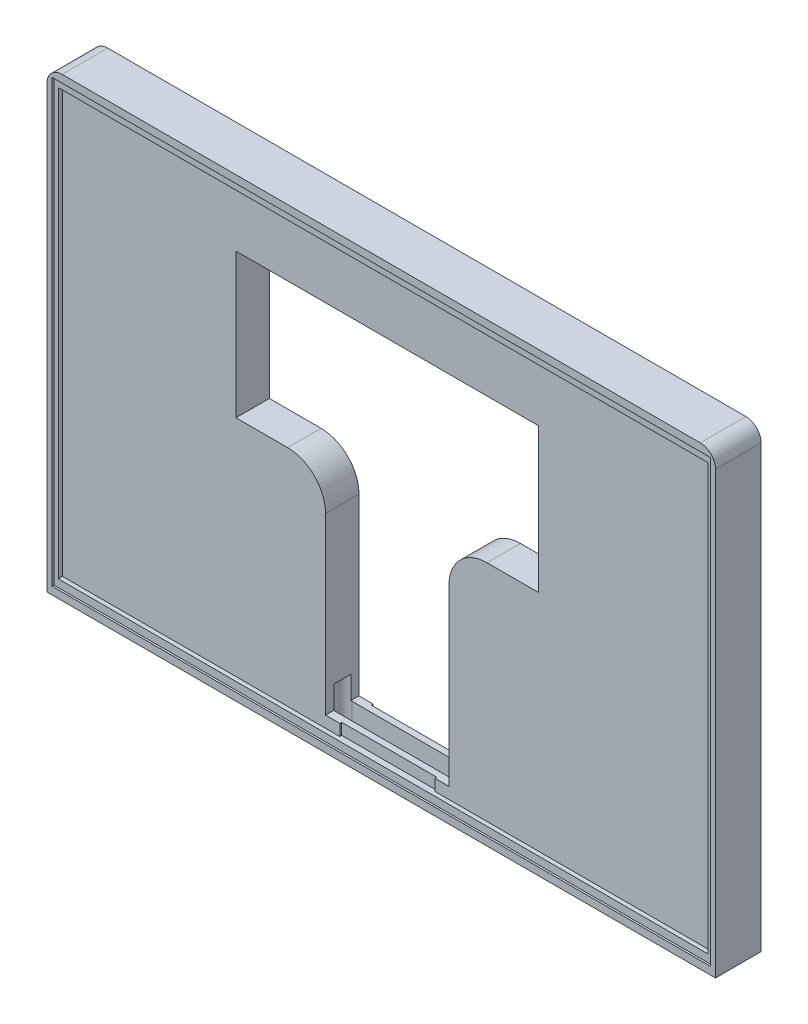
SolidWorks part; units mm, degrees
ref_plane "前视基准面" through (0, 0, 0) normal (0, 0, 1) x (1, 0, 0)
ref_plane "上视基准面" through (0, 0, 0) normal (0, 1, 0) x (1, 0, 0)
ref_plane "右视基准面" through (0, 0, 0) normal (1, 0, 0) x (0, 0, -1)
other "Configuration Table"
sketch "草图1" plane through (0, 0, 0) normal (0, 0, 1) x (1, 0, 0)
  line L0 (-88, 60) -> (-88, -60)
  line L1 (-88, -60) -> (88, -60)
  line L2 (88, -60) -> (88, 60)
  line L3 (88, 60) -> (-88, 60)
  line L4 (0, 145.8225) -> (0, -134.4269) construction
  line L5 (-152.9976, 0) -> (171.9904, 0) construction
  dimension "D1" = 176
  dimension "D2" = 120
extrude "凸台-拉伸1" add sketch "草图1" along normal blind 12
sketch "草图2" plane through (0, 0, 12) normal (0, 0, 1) x (1, 0, 0)
  line L0 (-111.1919, 0) -> (116.8836, 0) construction
  line L1 (0, 67.9619) -> (0, -74.6023) construction
  line L3 (-85.5, 56) -> (85.5, 56)
  line L4 (-85.5, 56) -> (-85.5, -56)
  line L5 (-85.5, -56) -> (85.5, -56)
  line L6 (85.5, 56) -> (85.5, -56)
  line L7 (-85.5, 56) -> (85.5, -56) construction
  line L8 (-85.5, -56) -> (85.5, 56) construction
  point P5 (0, 0)
  dimension "D1" = 171
  dimension "D2" = 112
extrude "切除-拉伸1" cut sketch "草图2" against normal blind 1.6
sketch "草图3" plane through (0, 0, 0) normal (0, 0, -1) x (-1, 0, 0)
  line L0 (-109.5657, 0) -> (110.3788, 0) construction
  line L1 (0, 67.4198) -> (0, -75.1443) construction
  line L3 (-85.5, 56) -> (85.5, 56)
  line L4 (-85.5, 56) -> (-85.5, -56)
  line L5 (-85.5, -56) -> (85.5, -56)
  line L6 (85.5, 56) -> (85.5, -56)
  line L7 (-85.5, 56) -> (85.5, -56) construction
  line L8 (-85.5, -56) -> (85.5, 56) construction
  point P5 (0, 0)
  dimension "D1" = 171
  dimension "D2" = 112
extrude "切除-拉伸2" cut sketch "草图3" against normal blind 1.6
sketch "草图5" plane through (0, 0, 0) normal (0, 0, -1) x (-1, 0, 0)
  line L1 (-86.7, 58) -> (86.7, 58)
  line L2 (-86.7, 58) -> (-86.7, -58)
  line L3 (-86.7, -58) -> (86.7, -58)
  line L4 (86.7, 58) -> (86.7, -58)
  line L5 (-86.7, 58) -> (86.7, -58) construction
  line L6 (-86.7, -58) -> (86.7, 58) construction
  point P0 (0, 0)
  dimension "D1" = 173.4
  dimension "D2" = 116
extrude "切除-拉伸3" cut sketch "草图5" against normal blind 0.5
sketch "草图6" plane through (0, 0, 12) normal (0, 0, 1) x (1, 0, 0)
  line L1 (-86.7, 58) -> (86.7, 58)
  line L2 (-86.7, 58) -> (-86.7, -58)
  line L3 (-86.7, -58) -> (86.7, -58)
  line L4 (86.7, 58) -> (86.7, -58)
  line L5 (-86.7, 58) -> (86.7, -58) construction
  line L6 (-86.7, -58) -> (86.7, 58) construction
  point P0 (0, 0)
  dimension "D1" = 173.4
  dimension "D2" = 116
extrude "切除-拉伸4" cut sketch "草图6" against normal blind 0.5
sketch "草图7" plane through (0, 0, 1.6) normal (0, 0, -1) x (-1, 0, 0)
  line L0 (0, 28.0765) -> (0, -41.7057) construction
  line L1 (-16.25, 3) -> (16.25, 3)
  line L2 (-16.25, 3) -> (-16.25, -53)
  line L3 (-16.25, -53) -> (16.25, -53)
  line L4 (16.25, 3) -> (16.25, -53)
  line L5 (-16.25, 3) -> (16.25, -53) construction
  line L6 (-16.25, -53) -> (16.25, 3) construction
  line L7 (-86.7, -58) -> (86.7, -58) construction
  point P0 (0, -25)
  dimension "D1" = 32.5
  dimension "D2" = 56
  dimension "D3" = 5
extrude "切除-拉伸5" cut sketch "草图7" against normal through all
sketch "草图8" plane through (0, 0, 1.6) normal (0, 0, -1) x (-1, 0, 0)
  line L0 (0, 36.1154) -> (0, -67.2843) construction
  line L1 (-12.5, -51) -> (-12.5, -56)
  line L3 (-85.5, -56) -> (85.5, -56) construction
  line L4 (-12.5, -56) -> (12.5, -56)
  line L5 (12.5, -56) -> (12.5, -51)
  line L6 (12.5, -51) -> (-12.5, -51)
  dimension "D1" = 25
  dimension "D2" = 5
extrude "切除-拉伸6" cut sketch "草图8" against normal blind 0.5
sketch "草图9" plane through (0, 0, 10.4) normal (0, 0, 1) x (1, 0, 0)
  line L0 (0, 18.0916) -> (0, -73.9247) construction
  line L1 (-12.5, -51) -> (-12.5, -56)
  line L3 (85.5, -56) -> (-85.5, -56) construction
  line L4 (-12.5, -56) -> (12.5, -56)
  line L5 (-85.5, -56) -> (85.5, -56) construction
  line L6 (12.5, -56) -> (12.5, -51)
  line L7 (12.5, -51) -> (-12.5, -51)
  dimension "D1" = 25
  dimension "D2" = 5
extrude "切除-拉伸7" cut sketch "草图9" against normal blind 0.5
sketch "草图10" plane through (0, 0, 10.4) normal (0, 0, 1) x (1, 0, 0)
  line L0 (0, 67.0133) -> (0, 14.2971) construction
  line L1 (-12.5, 56) -> (-12.5, 3)
  line L2 (-85.5, 56) -> (85.5, 56) construction
  line L3 (16.25, 3) -> (-16.25, 3) construction
  line L4 (-12.5, 3) -> (12.5, 3)
  line L5 (12.5, 3) -> (12.5, 56)
  line L6 (12.5, 56) -> (-12.5, 56)
  dimension "D1" = 25
sketch "草图11" plane through (0, 0, 1.6) normal (0, 0, -1) x (-1, 0, 0)
  line L0 (0, 66.8778) -> (0, 24.5964) construction
  line L1 (-33.5, 56) -> (-33.5, 3)
  line L2 (85.5, 56) -> (-85.5, 56) construction
  line L3 (16.25, 3) -> (-16.25, 3) construction
  line L4 (-33.5, 3) -> (33.5, 3)
  line L5 (33.5, 3) -> (33.5, 56)
  line L6 (33.5, 56) -> (-33.5, 56)
  dimension "D1" = 67
sketch "草图13" plane through (0, 60, 0) normal (0, 1, 0) x (1, 0, 0)
  line L0 (0, 12.7154) -> (0, -17.2798) construction
  line L4 (-13.75, -5) -> (13.75, -5) construction
  line L5 (-13.75, -2.75) -> (13.75, -2.75)
  line L6 (-13.75, -7.25) -> (13.75, -7.25)
  line L7 (88, -12) -> (88, 0) construction
  line L8 (88, -6) -> (-97.094, -6) construction
  arc A2 (-13.75, -2.75) -> (-13.75, -7.25) centre (-13.75, -5) ccw
  arc A3 (13.75, -7.25) -> (13.75, -2.75) centre (13.75, -5) ccw
  point P10 (0, -5)
  point P19 (-16, -5)
  point P20 (16, -5)
  dimension "D2" = 32
  dimension "D4" = 4.5
ref_plane "基准面1" through (0, 0, 7) normal (0, 0, 1) x (1, 0, 0)
sketch "草图16" plane through (-88, 0, 0) normal (-1, 0, 0) x (0, 0, 1)
  line L0 (0, -60) -> (-14.0954, -65.1303)
  line L1 (12, -60) -> (26.0954, -65.1303)
  line L2 (12, 60) -> (12, -60) construction
  line L3 (0, 60) -> (0, -60) construction
  line L4 (-14.0954, -65.1303) -> (-14.0954, -67.3303)
  line L5 (26.0954, -65.1303) -> (26.0954, -67.3303)
  line L6 (26.0954, -67.3303) -> (-14.0954, -67.3303)
  line L7 (0, -60) -> (12, -60)
  dimension "D1" = 15
  dimension "D2" = 15
  dimension "D3" = 110
  dimension "D4" = 110
  dimension "D5" = 2.2
fillet "圆角1" radius 4 1 edges at (-88, 60, 6)
fillet "圆角2" radius 4 1 edges at (88, 60, 6)
ref_plane "基准面2" through (-16.25, 0, 0) normal (1, 0, 0) x (0, 0, -1)
sketch "草图18" plane through (-16.25, 0, 0) normal (1, 0, 0) x (0, 0, -1)
  line L0 (-1.6, -50) -> (-3.1, -50)
  line L1 (-1.6, -53) -> (-1.6, 3) construction
  line L2 (-3.1, -50) -> (-3.1, -53)
  line L3 (-10.4, -53) -> (-1.6, -53) construction
  line L4 (-3.1, -53) -> (-1.6, -53)
  line L5 (-1.6, -53) -> (-1.6, -50)
  line L6 (-10.4, -50) -> (-10.4, -53)
  line L7 (-10.4, 3) -> (-10.4, -53) construction
  line L8 (-10.4, -53) -> (-8.9, -53)
  line L9 (-8.9, -53) -> (-8.9, -50)
  line L10 (-8.9, -50) -> (-10.4, -50)
  dimension "D1" = 1.5
  dimension "D2" = 1.5
  dimension "D3" = 3
  dimension "D4" = 3
ref_plane "基准面3" through (16.25, 0, 0) normal (-1, 0, 0) x (0, 0, 1)
sketch "草图19" plane through (16.25, 0, 0) normal (-1, 0, 0) x (0, 0, 1)
  line L0 (1.6, -8.7196) -> (2.4, -8.7196)
  line L1 (1.6, 3) -> (1.6, -53) construction
  line L2 (2.4, -8.7196) -> (2.4, -53)
  line L3 (10.4, -53) -> (1.6, -53) construction
  line L4 (2.4, -53) -> (1.6, -53)
  line L5 (1.6, -53) -> (1.6, -8.7196)
  dimension "D1" = 0.8
sketch "草图20" plane through (16.25, 0, 0) normal (-1, 0, 0) x (0, 0, 1)
  line L0 (10.4, -50) -> (8.9, -50)
  line L1 (10.4, -53) -> (10.4, 3) construction
  line L2 (8.9, -50) -> (8.9, -53)
  line L3 (10.4, -53) -> (1.6, -53) construction
  line L4 (8.9, -53) -> (10.4, -53)
  line L5 (10.4, -53) -> (10.4, -50)
  line L6 (1.6, -50) -> (3.1, -50)
  line L7 (1.6, 3) -> (1.6, -53) construction
  line L8 (3.1, -50) -> (3.1, -53)
  line L9 (3.1, -53) -> (1.6, -53)
  line L10 (1.6, -53) -> (1.6, -50)
  dimension "D1" = 1.5
  dimension "D2" = 1.5
  dimension "D3" = 3
ref_plane "基准面5" through (0, 0, 2.1) normal (0, 0, -1) x (-1, 0, 0)
sketch "草图21" plane through (0, 0, 2.1) normal (0, 0, -1) x (-1, 0, 0)
  line L0 (-12.5, -22.083) -> (-12.5, -38.083)
  line L1 (-12.5, -53) -> (-12.5, -56) construction
  line L2 (-12.5, -53) -> (-12.5, -56) construction
  line L3 (-12.5, -38.083) -> (12.5, -38.083)
  line L4 (12.5, -56) -> (12.5, -53) construction
  line L5 (12.5, -38.083) -> (12.5, -22.083)
  line L6 (12.5, -22.083) -> (-12.5, -22.083)
  dimension "D1" = 16
ref_plane "基准面15" through (0, 0, 9.9) normal (0, 0, 1) x (1, 0, 0)
ref_plane "基准面16" through (0, 0, 2.1) normal (0, 0, -1) x (-1, 0, 0)
ref_plane "基准面17" through (-88, 0, 0) normal (-1, 0, 0) x (0, 0, 1)
ref_plane "基准面18" through (0, -60, 0) normal (0, -1, 0) x (-1, 0, 0)
sketch "草图28" plane through (0, -60, 0) normal (0, -1, 0) x (-1, 0, 0)
  line L0 (-88, -6) -> (90.5933, -6) construction
  line L1 (-88, -12) -> (-88, 0) construction
  line L2 (0, 32.1995) -> (0, -32.8488) construction
  circle A0 centre (-72, -6) radius 2.75
  circle A1 centre (-38, -6) radius 2.75
  circle A2 centre (38, -6) radius 2.75
  circle A3 centre (72, -6) radius 2.75
  dimension "D1" = 5.5
  dimension "D2" = 5.5
  dimension "D3" = 5.5
  dimension "D4" = 5.5
  dimension "D5" = 38
  dimension "D6" = 38
  dimension "D7" = 72
  dimension "D8" = 72
extrude "切除-拉伸16" cut sketch "草图28" against normal blind 5.5
sketch "草图29" plane through (0, -60, 0) normal (0, -1, 0) x (1, 0, 0)
  line L0 (-16, 6) -> (16, 6) construction
  line L1 (-16, 8.25) -> (16, 8.25)
  line L2 (-16, 3.75) -> (16, 3.75)
  line L3 (-1037.7858, 6) -> (48962.2142, 6) construction
  line L4 (0, 0) -> (0, 50000) construction
  line L5 (-88, 0) -> (88, 0) construction
  line L9 (-88, 12) -> (88, 12) construction
  arc A0 (-16, 8.25) -> (-16, 3.75) centre (-16, 6) ccw
  arc A1 (16, 3.75) -> (16, 8.25) centre (16, 6) ccw
  point P2 (0, 6)
  point P13 (0, 0)
  dimension "D1" = 4.5
  dimension "D2" = 32
extrude "切除-拉伸17" cut sketch "草图29" against normal blind 13
sketch "草图31" plane through (0, 0, 1.6) normal (0, 0, -1) x (-1, 0, 0)
  line L1 (-39.8301, 41) -> (39.8301, 41)
  line L2 (-39.8301, 41) -> (-39.8301, 3)
  line L3 (-39.8301, 3) -> (39.8301, 3)
  line L4 (39.8301, 41) -> (39.8301, 3)
  line L5 (-39.8301, 41) -> (39.8301, 3) construction
  line L6 (-39.8301, 3) -> (39.8301, 41) construction
  point P0 (0, 22)
  dimension "D1" = 38
extrude "切除-拉伸18" cut sketch "草图31" against normal through all
fillet "圆角3" radius 10 1 edges at (-16.25, 3, 6)
fillet "圆角4" radius 10 1 edges at (16.25, 3, 6)
sketch "草图33" plane through (16.25, 0, 0) normal (-1, 0, 0) x (0, 0, 1)
  line L0 (1.6, -53) -> (1.6, -51.8)
  line L1 (1.6, -7) -> (1.6, -53) construction
  line L2 (1.6, -51.8) -> (1.9, -51.8)
  line L3 (1.9, -51.8) -> (1.9, -53)
  line L4 (3.7639, -53) -> (1.6, -53) construction
  line L5 (1.9, -53) -> (1.6, -53)
  line L6 (10.4, -53) -> (10.4, -51.8)
  line L7 (10.4, -53) -> (10.4, -7) construction
  line L8 (10.4, -51.8) -> (10.1, -51.8)
  line L9 (10.1, -51.8) -> (10.1, -53)
  line L10 (10.4, -53) -> (8.2361, -53) construction
  line L11 (10.1, -53) -> (10.4, -53)
  dimension "D1" = 1.2
  dimension "D2" = 1.2
  dimension "D3" = 0.3
  dimension "D4" = 0.3
sketch "草图34" plane through (-16.25, 0, 0) normal (1, 0, 0) x (0, 0, -1)
  line L0 (-1.6, -9.5) -> (-2.1, -9.5)
  line L1 (-1.6, -53) -> (-1.6, -7) construction
  line L2 (-2.1, -9.5) -> (-2.1, -13)
  line L3 (-2.1, -13) -> (-1.6, -13)
  line L4 (-3.7639, -53) -> (-1.6, -53) construction
  line L5 (-10.4, -9.5) -> (-9.9, -9.5)
  line L6 (-10.4, -7) -> (-10.4, -53) construction
  line L7 (-9.9, -9.5) -> (-9.9, -13)
  line L8 (-9.9, -13) -> (-10.4, -13)
  line L9 (-10.4, -13) -> (-10.4, -9.5)
  line L10 (-1.6, -9.5) -> (-1.6, -13)
  dimension "D1" = 40
  dimension "D2" = 0.5
  dimension "D3" = 0.5
  dimension "D4" = 3.5
sketch "草图35" plane through (16.25, 0, 0) normal (-1, 0, 0) x (0, 0, 1)
  line L0 (1.6146, -9.5) -> (1.6146, -13)
  line L1 (1.6146, -13) -> (2.1146, -13)
  line L2 (2.1146, -13) -> (2.1146, -9.5)
  line L3 (2.1146, -9.5) -> (1.6146, -9.5)
  line L4 (10.4, -9.5) -> (9.9, -9.5)
  line L5 (10.4, -53) -> (10.4, -7) construction
  line L6 (9.9, -9.5) -> (9.9, -13)
  line L7 (9.9, -13) -> (10.4, -13)
  line L8 (10.4, -13) -> (10.4, -9.5)
  line L9 (3.7639, -53) -> (1.6, -53) construction
  dimension "D1" = 40
  dimension "D2" = 0.5
  dimension "D3" = 3.5
  dimension "D4" = 0.5
  dimension "D5" = 3.5
